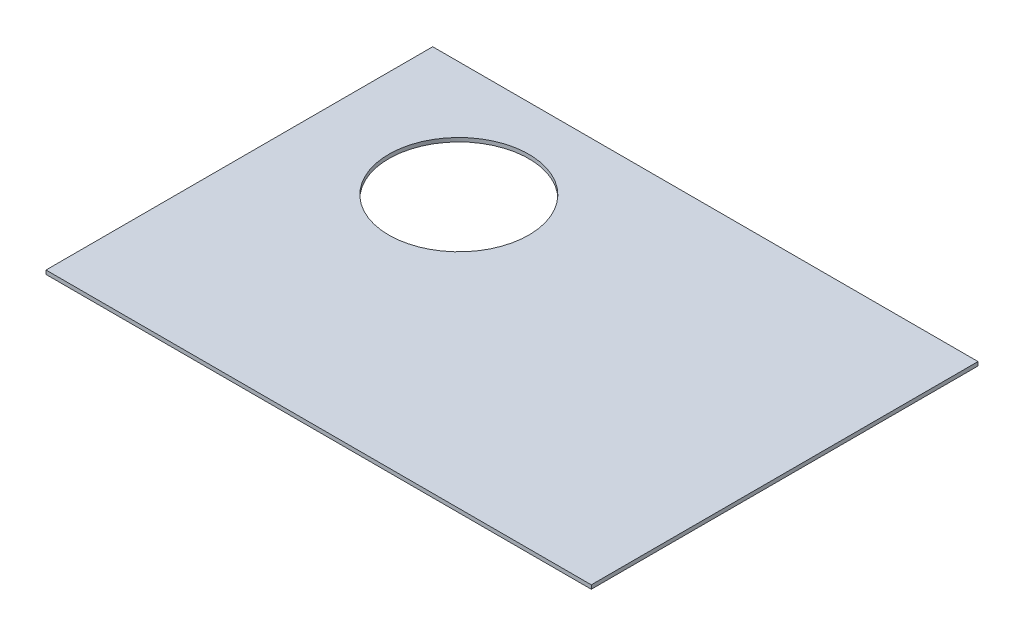
SolidWorks part; units mm, degrees
ref_plane "Front Plane" through (0, 0, 0) normal (0, 0, 1) x (1, 0, 0)
ref_plane "Top Plane" through (0, 0, 0) normal (0, 1, 0) x (1, 0, 0)
ref_plane "Right Plane" through (0, 0, 0) normal (1, 0, 0) x (0, 0, -1)
sketch "Sketch1" plane through (0, 0, 0) normal (0, 1, 0) x (1, 0, 0)
  line L0 (401.6375, 0) -> (447.675, 0)
  line L1 (0, 0) -> (46.0375, 0)
  line L2 (0, 0) -> (0, 317.5)
  line L3 (0, 317.5) -> (447.675, 317.5)
  line L4 (447.675, 0) -> (447.675, 317.5)
  line L6 (46.0375, 0) -> (46.0375, -3.175) construction
  line L7 (46.0375, -3.175) -> (401.6375, -3.175) construction
  line L8 (401.6375, 0) -> (401.6375, -3.175) construction
  line L9 (46.0375, 0) -> (401.6375, 0)
  point P9 (223.8375, -3.175)
  point P10 (223.8375, 317.5)
  dimension "D1" = 447.675
  dimension "D2" = 317.5
  dimension "D3" = 355.6
  dimension "D4" = 3.175
extrude "Boss-Extrude1" add sketch "Sketch1" along normal blind 3.175
ref_plane "Plane1" through (223.8375, 0, 0) normal (-1, 0, 0) x (0, 0, 1)
sketch "Sketch4" plane through (0, 3.175, 0) normal (0, 1, 0) x (1, 0, 0)
  line L0 (223.8375, 1.7463) -> (223.8375, -1.7463) construction
  line L1 (55.8875, 283.0438) -> (175.8875, 283.0438) construction
  line L2 (55.8875, 283.0438) -> (55.8875, 163.0437) construction
  line L3 (55.8875, 163.0437) -> (175.8875, 163.0437) construction
  line L4 (175.8875, 283.0438) -> (175.8875, 163.0437) construction
  line L6 (62.7063, 276.225) -> (169.0687, 276.225) construction
  line L8 (62.7063, 276.225) -> (62.7063, 169.8625) construction
  line L9 (62.7063, 169.8625) -> (169.0687, 169.8625) construction
  line L10 (169.0687, 276.225) -> (169.0687, 169.8625) construction
  circle A4 centre (115.8875, 223.0438) radius 57.5
  point P5 (0, 0)
  point P7 (0, 0)
  point P12 (0, 0)
  point P13 (115.8875, 283.0438)
  point P21 (115.8875, 276.225)
  point P26 (175.8875, 223.0438)
  point P33 (169.0687, 223.0438)
  dimension "D9" = 115
  dimension "D1" = 120
  dimension "D2" = 120
  dimension "D4" = 106.3625
  dimension "D5" = 163.0437
  dimension "D10" = 107.95
extrude "Cut-Extrude3" cut sketch "Sketch4" against normal through all
